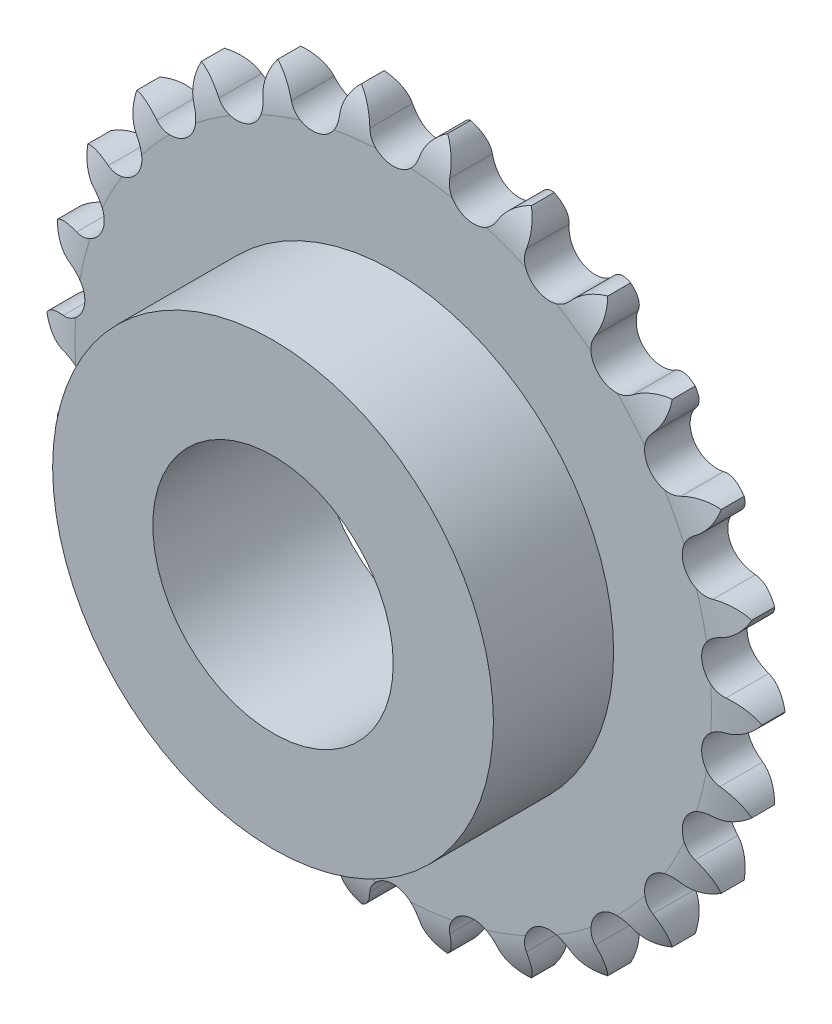
SolidWorks part; units mm, degrees
ref_plane "Plan de face" through (0, 0, 0) normal (0, 0, 1) x (1, 0, 0)
ref_plane "Plan de dessus" through (0, 0, 0) normal (0, 1, 0) x (1, 0, 0)
ref_plane "Plan de droite" through (0, 0, 0) normal (1, 0, 0) x (0, 0, -1)
sketch "Esquisse1" plane through (0, 0, 0) normal (0, 0, 1) x (1, 0, 0)
  line L0 (0, 56.7181) -> (0, 0) construction
  circle A3 centre (0, 0) radius 49.259
  arc A4 (3.9337, 52.412) -> (-3.9337, 52.412) centre (0, 53.2894) cw
  arc A5 (3.9337, 52.412) -> (6.9009, 56.2967) centre (9.6207, 51.1437) cw
  circle A6 centre (0, 0) radius 19.05
  arc A7 (-3.9337, 52.412) -> (-6.9009, 56.2967) centre (-9.6207, 51.1437) ccw
  arc A8 (16.3624, 49.9477) -> (20.1731, 53.0093) centre (21.5806, 47.3552) cw
  arc A9 (16.3624, 49.9477) -> (8.7236, 51.8304) centre (12.753, 51.7409) cw
  arc A10 (8.7236, 51.8304) -> (6.7723, 56.3123) centre (2.8984, 51.96) ccw
  arc A11 (27.8402, 44.5805) -> (32.2728, 46.6412) centre (32.2863, 40.8146) cw
  arc A12 (27.8402, 44.5805) -> (20.874, 48.2366) centre (24.7648, 47.1854) cw
  arc A13 (20.874, 48.2366) -> (20.0519, 53.0553) centre (15.249, 49.7565) ccw
  arc A14 (37.7, 36.6225) -> (42.497, 37.5625) centre (41.1157, 31.9019) cw
  arc A15 (37.7, 36.6225) -> (31.8112, 41.8395) centre (35.3374, 39.8877) cw
  arc A16 (31.8112, 41.8395) -> (32.1662, 46.7148) centre (26.7134, 44.6613) ccw
  arc A17 (45.3689, 26.5361) -> (50.2514, 26.3008) centre (47.5556, 21.1353) cw
  arc A18 (45.3689, 26.5361) -> (40.8997, 33.0108) centre (43.8563, 30.2718) cw
  arc A19 (40.8997, 33.0108) -> (42.4111, 37.6595) centre (36.6253, 36.9706) ccw
  arc A20 (50.401, 14.9075) -> (55.0854, 13.5106) centre (51.2317, 9.1403) cw
  arc A21 (50.401, 14.9075) -> (47.6112, 22.2636) centre (49.8264, 18.8967) cw
  arc A22 (47.6112, 22.2636) -> (50.1912, 26.4155) centre (44.4087, 27.1313) ccw
  arc A23 (52.5041, 2.4126) -> (56.718, -0.0648) centre (51.9305, -3.3858) cw
  arc A24 (52.5041, 2.4126) -> (51.5557, 10.2226) centre (52.9008, 6.4233) cw
  arc A25 (51.5557, 10.2226) -> (55.0544, 13.6364) centre (49.6112, 15.7152) ccw
  arc A26 (51.5557, -10.2226) -> (55.0544, -13.6364) centre (49.6112, -15.7152) cw
  arc A27 (51.5557, -10.2226) -> (52.5041, -2.4126) centre (52.9008, -6.4233) cw
  arc A28 (52.5041, -2.4126) -> (56.718, 0.0648) centre (51.9305, 3.3858) ccw
  arc A29 (47.6112, -22.2636) -> (50.1912, -26.4155) centre (44.4087, -27.1313) cw
  arc A30 (47.6112, -22.2636) -> (50.401, -14.9075) centre (49.8264, -18.8967) cw
  arc A31 (50.401, -14.9075) -> (55.0854, -13.5106) centre (51.2317, -9.1403) ccw
  arc A32 (40.8997, -33.0108) -> (42.4111, -37.6595) centre (36.6253, -36.9706) cw
  arc A33 (40.8997, -33.0108) -> (45.3689, -26.5361) centre (43.8563, -30.2718) cw
  arc A34 (45.3689, -26.5361) -> (50.2514, -26.3008) centre (47.5556, -21.1353) ccw
  arc A35 (31.8112, -41.8395) -> (32.1662, -46.7148) centre (26.7134, -44.6613) cw
  arc A36 (31.8112, -41.8395) -> (37.7, -36.6225) centre (35.3374, -39.8877) cw
  arc A37 (37.7, -36.6225) -> (42.497, -37.5625) centre (41.1157, -31.9019) ccw
  arc A38 (20.874, -48.2366) -> (20.0519, -53.0553) centre (15.249, -49.7565) cw
  arc A39 (20.874, -48.2366) -> (27.8402, -44.5805) centre (24.7648, -47.1854) cw
  arc A40 (27.8402, -44.5805) -> (32.2728, -46.6412) centre (32.2863, -40.8146) ccw
  arc A41 (8.7236, -51.8304) -> (6.7723, -56.3123) centre (2.8984, -51.96) cw
  arc A42 (8.7236, -51.8304) -> (16.3624, -49.9477) centre (12.753, -51.7409) cw
  arc A43 (16.3624, -49.9477) -> (20.1731, -53.0093) centre (21.5806, -47.3552) ccw
  arc A44 (-3.9337, -52.412) -> (-6.9009, -56.2967) centre (-9.6207, -51.1437) cw
  arc A45 (-3.9337, -52.412) -> (3.9337, -52.412) centre (0, -53.2894) cw
  arc A46 (3.9337, -52.412) -> (6.9009, -56.2967) centre (9.6207, -51.1437) ccw
  arc A47 (-16.3624, -49.9477) -> (-20.1731, -53.0093) centre (-21.5806, -47.3552) cw
  arc A48 (-16.3624, -49.9477) -> (-8.7236, -51.8304) centre (-12.753, -51.7409) cw
  arc A49 (-8.7236, -51.8304) -> (-6.7723, -56.3123) centre (-2.8984, -51.96) ccw
  arc A50 (-27.8402, -44.5805) -> (-32.2728, -46.6412) centre (-32.2863, -40.8146) cw
  arc A51 (-27.8402, -44.5805) -> (-20.874, -48.2366) centre (-24.7648, -47.1854) cw
  arc A52 (-20.874, -48.2366) -> (-20.0519, -53.0553) centre (-15.249, -49.7565) ccw
  arc A53 (-37.7, -36.6225) -> (-42.497, -37.5625) centre (-41.1157, -31.9019) cw
  arc A54 (-37.7, -36.6225) -> (-31.8112, -41.8395) centre (-35.3374, -39.8877) cw
  arc A55 (-31.8112, -41.8395) -> (-32.1662, -46.7148) centre (-26.7134, -44.6613) ccw
  arc A56 (-45.3689, -26.5361) -> (-50.2514, -26.3008) centre (-47.5556, -21.1353) cw
  arc A57 (-45.3689, -26.5361) -> (-40.8997, -33.0108) centre (-43.8563, -30.2718) cw
  arc A58 (-40.8997, -33.0108) -> (-42.4111, -37.6595) centre (-36.6253, -36.9706) ccw
  arc A59 (-50.401, -14.9075) -> (-55.0854, -13.5106) centre (-51.2317, -9.1403) cw
  arc A60 (-50.401, -14.9075) -> (-47.6112, -22.2636) centre (-49.8264, -18.8967) cw
  arc A61 (-47.6112, -22.2636) -> (-50.1912, -26.4155) centre (-44.4087, -27.1313) ccw
  arc A62 (-52.5041, -2.4126) -> (-56.718, 0.0648) centre (-51.9305, 3.3858) cw
  arc A63 (-52.5041, -2.4126) -> (-51.5557, -10.2226) centre (-52.9008, -6.4233) cw
  arc A64 (-51.5557, -10.2226) -> (-55.0544, -13.6364) centre (-49.6112, -15.7152) ccw
  arc A65 (-51.5557, 10.2226) -> (-55.0544, 13.6364) centre (-49.6112, 15.7152) cw
  arc A66 (-51.5557, 10.2226) -> (-52.5041, 2.4126) centre (-52.9008, 6.4233) cw
  arc A67 (-52.5041, 2.4126) -> (-56.718, -0.0648) centre (-51.9305, -3.3858) ccw
  arc A68 (-47.6112, 22.2636) -> (-50.1912, 26.4155) centre (-44.4087, 27.1313) cw
  arc A69 (-47.6112, 22.2636) -> (-50.401, 14.9075) centre (-49.8264, 18.8967) cw
  arc A70 (-50.401, 14.9075) -> (-55.0854, 13.5106) centre (-51.2317, 9.1403) ccw
  arc A71 (-40.8997, 33.0108) -> (-42.4111, 37.6595) centre (-36.6253, 36.9706) cw
  arc A72 (-40.8997, 33.0108) -> (-45.3689, 26.5361) centre (-43.8563, 30.2718) cw
  arc A73 (-45.3689, 26.5361) -> (-50.2514, 26.3008) centre (-47.5556, 21.1353) ccw
  arc A74 (-31.8112, 41.8395) -> (-32.1662, 46.7148) centre (-26.7134, 44.6613) cw
  arc A75 (-31.8112, 41.8395) -> (-37.7, 36.6225) centre (-35.3374, 39.8877) cw
  arc A76 (-37.7, 36.6225) -> (-42.497, 37.5625) centre (-41.1157, 31.9019) ccw
  arc A77 (-20.874, 48.2366) -> (-20.0519, 53.0553) centre (-15.249, 49.7565) cw
  arc A78 (-20.874, 48.2366) -> (-27.8402, 44.5805) centre (-24.7648, 47.1854) cw
  arc A79 (-27.8402, 44.5805) -> (-32.2728, 46.6412) centre (-32.2863, 40.8146) ccw
  arc A80 (-8.7236, 51.8304) -> (-6.7723, 56.3123) centre (-2.8984, 51.96) cw
  arc A81 (-8.7236, 51.8304) -> (-16.3624, 49.9477) centre (-12.753, 51.7409) cw
  arc A82 (-16.3624, 49.9477) -> (-20.1731, 53.0093) centre (-21.5806, 47.3552) ccw
  point P16 (-9.6207, 51.1437)
  point P194 (0, 0)
  dimension "D1" = 5.8267
  dimension "D2" = 5.8267
  dimension "D3" = 26
extrude "Boss.-Extru.2" add sketch "Esquisse1" along normal mid plane 7.213
sketch "Esquisse2" plane through (0, 0, 0) normal (1, 0, 0) x (0, 0, -1)
  line L0 (0, 56.2592) -> (0, 46.6405) construction
  line L3 (-3.6065, 56.2592) -> (3.6065, 56.2592) construction
  line L4 (-3.6065, 46.6405) -> (3.6065, 46.6405) construction
  line L5 (-7.9807, 46.1139) -> (-7.9807, 56.89)
  line L6 (-7.9807, 56.89) -> (-1.6858, 56.89)
  line L7 (-7.9807, 50.419) -> (-3.9808, 50.419)
  line L8 (-3.9808, 50.419) -> (-3.6065, 50.419)
  line L9 (0, 0) -> (-24.4691, 0) construction
  line L10 (-3.6065, 52.9897) -> (-3.6065, 48.2366) construction
  line L11 (7.9807, 50.419) -> (3.9808, 50.419)
  line L12 (7.9807, 46.1139) -> (7.9807, 56.89)
  line L13 (7.9807, 56.89) -> (1.6858, 56.89)
  line L14 (0, 0) -> (35.9186, 0) construction
  line L15 (-1.6858, 56.89) -> (1.6858, 56.89)
  line L16 (-24.4691, 0) -> (91.965, 0) construction
  line L17 (3.6065, 50.419) -> (3.9808, 50.419)
  arc A0 (-1.6858, 56.89) -> (-3.6065, 50.419) centre (9.0911, 50.1707) ccw
  arc A1 (1.6858, 56.89) -> (3.6065, 50.419) centre (-9.0911, 50.1707) cw
  point P16 (-3.6065, 50.419)
  dimension "D3" = 12.7
  dimension "D1" = 50.419
  dimension "D2" = 56.89
  dimension "D4" = 0
revolve "Enlèvement de matière-Révolution2" cut sketch "Esquisse2" angle 360 about L16
sketch "Esquisse3" plane through (0, 0, 0) normal (1, 0, 0) x (0, 0, -1)
  line L0 (0, 0) -> (-42.9031, 0) construction
  point P0 (-3.6065, 19.05)
  point P1 (-3.6065, -19.05)
sketch "Esquisse4" plane through (0, 0, 3.6065) normal (0, 0, 1) x (1, 0, 0)
  circle A0 centre (0, 0) radius 34.925
  circle A1 centre (0, 0) radius 19.05
  dimension "D1" = 69.85
  dimension "D2" = 38.1
extrude "Boss.-Extru.3" add sketch "Esquisse4" along normal blind 19.05
sketch "Esquisse5" plane through (0, 0, 0) normal (0, 0, 1) x (1, 0, 0)
  circle A0 centre (0, 0) radius 50.419
